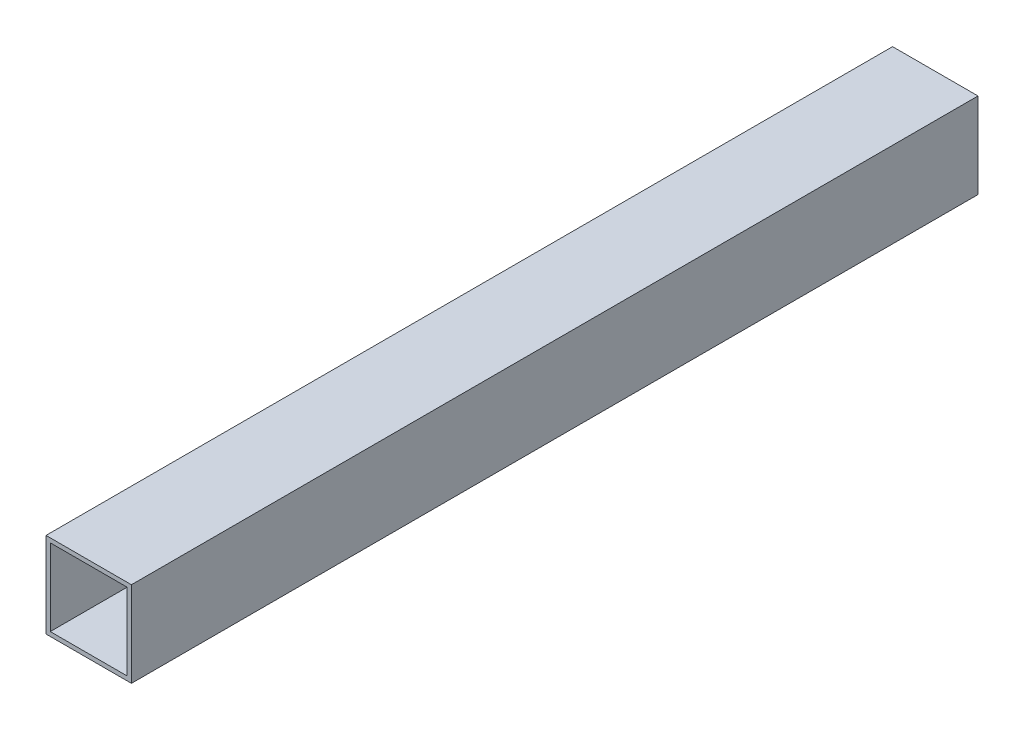
SolidWorks part; units mm, degrees
ref_plane "Front Plane" through (0, 0, 0) normal (0, 0, 1) x (1, 0, 0)
ref_plane "Top Plane" through (0, 0, 0) normal (0, 1, 0) x (1, 0, 0)
ref_plane "Right Plane" through (0, 0, 0) normal (1, 0, 0) x (0, 0, -1)
sketch "Sketch1" plane through (0, 0, 0) normal (0, 0, 1) x (1, 0, 0)
  line L1 (-9, -9) -> (9, -9)
  line L2 (-9, -9) -> (-9, 9)
  line L3 (-9, 9) -> (9, 9)
  line L4 (9, -9) -> (9, 9)
  line L5 (-9, -9) -> (9, 9) construction
  line L6 (-9, 9) -> (9, -9) construction
  line L7 (-10, -10) -> (10, -10)
  line L8 (-10, -10) -> (-10, 10)
  line L9 (-10, 10) -> (10, 10)
  line L10 (10, -10) -> (10, 10)
  line L11 (-10, -10) -> (10, 10) construction
  line L12 (-10, 10) -> (10, -10) construction
  point P0 (0, 0)
  point P6 (0, 0)
  dimension "D1" = 18
  dimension "D2" = 20
extrude "Boss-Extrude1" add sketch "Sketch1" along normal blind 198.2
